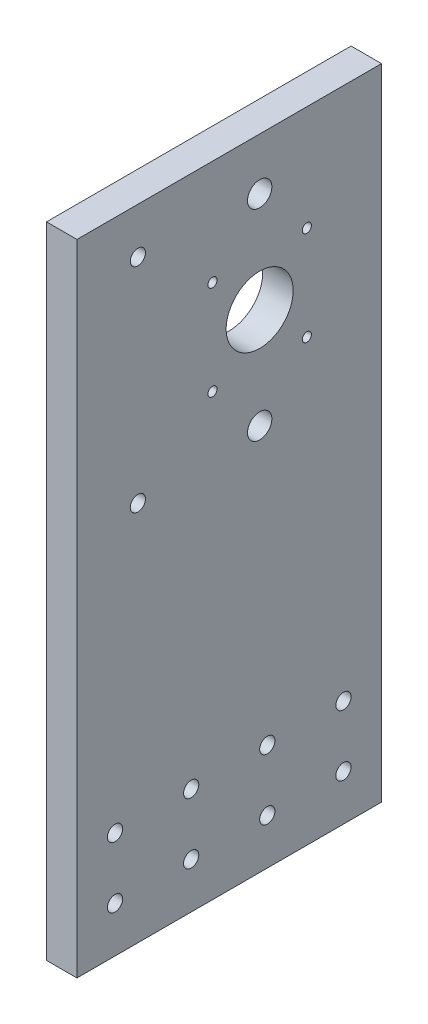
SolidWorks part; units mm, degrees
ref_plane "Front Plane" through (0, 0, 0) normal (0, 0, 1) x (1, 0, 0)
ref_plane "Top Plane" through (0, 0, 0) normal (0, 1, 0) x (1, 0, 0)
ref_plane "Right Plane" through (0, 0, 0) normal (1, 0, 0) x (0, 0, -1)
sketch "Sketch2" plane through (0, 0, 0) normal (1, 0, 0) x (0, 0, -1)
  line L0 (-60, 55) -> (40, 55) construction
  line L1 (40, -105) -> (-60, -105)
  line L2 (40, -105) -> (40, 105)
  line L3 (40, 105) -> (-60, 105)
  line L4 (-60, -105) -> (-60, 105)
  line L5 (40, -105) -> (-60, 105) construction
  line L6 (40, 105) -> (-60, -105) construction
  circle A0 centre (0, 88) radius 4
  circle A1 centre (0, 22) radius 4
  point P0 (0, 0)
  point P15 (-10, 0)
  dimension "D3" = 8
  dimension "D1" = 100
  dimension "D2" = 210
  dimension "D4" = 66
  dimension "D5" = 50
  dimension "D6" = 10
extrude "Boss-Extrude1" add sketch "Sketch2" along normal blind 10
sketch "Sketch3" plane through (10, 0, 0) normal (1, 0, 0) x (0, 0, -1)
  line L0 (-10, -105) -> (-10, -55) construction
  line L3 (-60, -105) -> (40, -105) construction
  line L5 (-35, -105) -> (-35, -55) construction
  line L6 (-10, -80) -> (-35, -80) construction
  line L8 (-35, -80) -> (-60, -80) construction
  line L9 (-60, 105) -> (-60, -105) construction
  circle A17 centre (-22.5, -70) radius 2.5
  circle A18 centre (-47.5, -70) radius 2.5
  circle A19 centre (-47.5, -90) radius 2.5
  circle A20 centre (-22.5, -90) radius 2.5
  circle A21 centre (2.5, -90) radius 2.5
  circle A22 centre (27.5, -90) radius 2.5
  circle A23 centre (27.5, -70) radius 2.5
  circle A24 centre (2.5, -70) radius 2.5
  point P15 (-22.5, -80)
  dimension "D1" = 25
  dimension "D2" = 25
  dimension "D3" = 5
  dimension "D4" = 20
extrude "mount" cut sketch "Sketch3" against normal through all
sketch "Sketch7" plane through (10, 0, 0) normal (1, 0, 0) x (0, 0, -1)
  line L0 (40, 105) -> (-60, 105) construction
  line L1 (-60, 105) -> (-60, -105) construction
  line L2 (0, 55) -> (-60, 55) construction
  line L3 (0, 88) -> (0, 22) construction
  circle A0 centre (-40, 90) radius 2.5
  circle A1 centre (-40, 20) radius 2.5
  dimension "D3" = 5
  dimension "D1" = 15
  dimension "D2" = 20
extrude "support_profile_mount" cut sketch "Sketch7" against normal through all
sketch "Sketch5" plane through (10, 0, 0) normal (1, 0, 0) x (0, 0, -1)
  line L0 (-60, 55) -> (40, 55) construction
  line L1 (-60, 105) -> (-60, -105) construction
  line L2 (40, -105) -> (40, 105) construction
  circle A0 centre (0, 22) radius 4 construction
  circle A1 centre (0, 88) radius 4 construction
  circle A2 centre (0, 55) radius 8.5
  dimension "D1" = 17
extrude "bearing_mount" [suppressed] cut sketch "Sketch5" against normal through all
sketch "Sketch4" plane through (10, 0, 0) normal (1, 0, 0) x (0, 0, -1)
  line L0 (-60, 55) -> (40, 55) construction
  line L1 (-60, 105) -> (-60, -105) construction
  line L2 (40, -105) -> (40, 105) construction
  line L3 (0, 55) -> (0, 0) construction
  circle A0 centre (0, 88) radius 4 construction
  circle A1 centre (0, 22) radius 4 construction
  circle A2 centre (0, 55) radius 11
  circle A3 centre (-15.5, 70.5) radius 1.5
  circle A4 centre (15.5, 70.5) radius 1.5
  circle A5 centre (-15.5, 39.5) radius 1.5
  circle A6 centre (15.5, 39.5) radius 1.5
  dimension "D1" = 22
  dimension "D2" = 3
  dimension "D3" = 31
  dimension "D4" = 31
extrude "stepper_mount" cut sketch "Sketch4" against normal through all
